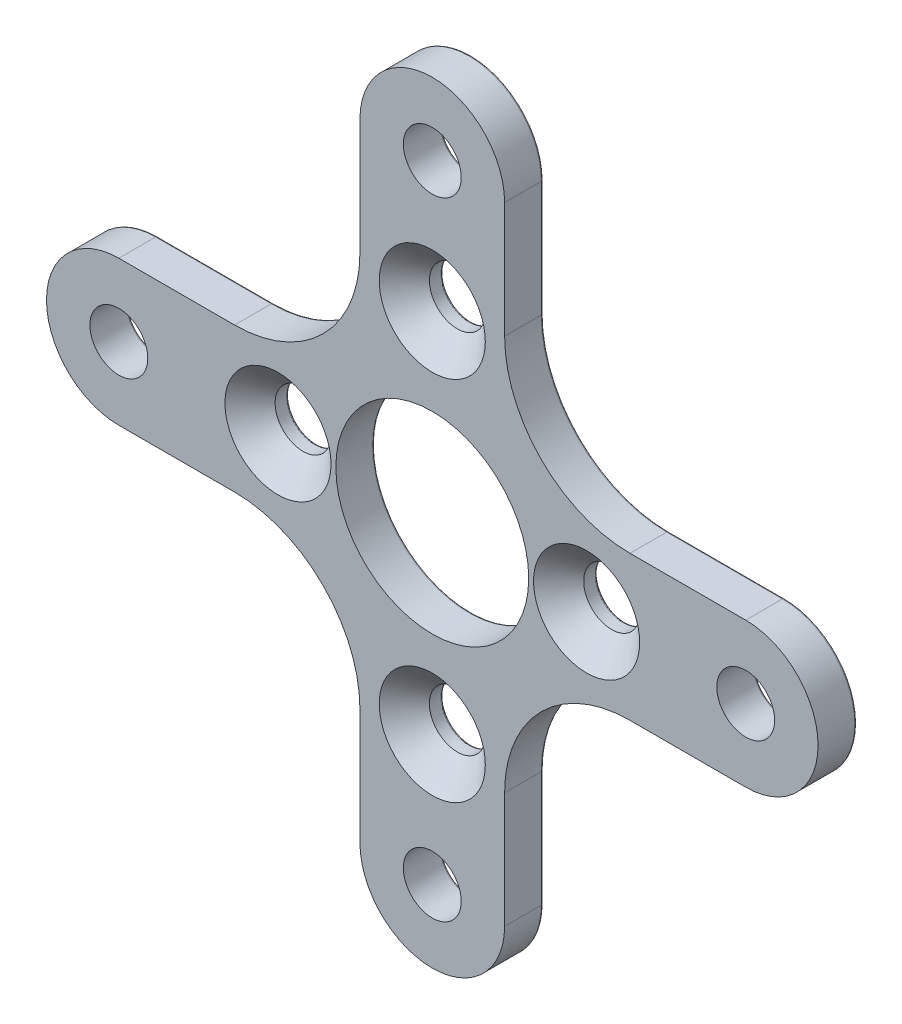
SolidWorks part; units mm, degrees
material "1060-H18 Rod (SS)"
ref_plane "Plan de face" through (0, 0, 0) normal (0, 0, 1) x (1, 0, 0)
ref_plane "Plan de dessus" through (0, 0, 0) normal (0, 1, 0) x (1, 0, 0)
ref_plane "Plan de droite" through (0, 0, 0) normal (1, 0, 0) x (0, 0, -1)
sketch "Esquisse1" plane through (0, 0, 0) normal (0, 0, 1) x (1, 0, 0)
  line L0 (-3.75, 16.25) -> (-3.75, 10.25)
  line L1 (-10.25, 3.75) -> (-16.25, 3.75)
  line L2 (-3.75, 16.25) -> (0, 16.25) construction
  line L3 (-16.25, 3.75) -> (-16.25, 0) construction
  line L4 (0, -16.25) -> (0, 16.25) construction
  line L5 (-16.25, 0) -> (0, 0) construction
  line L6 (0, 20) -> (0, 16.25) construction
  line L7 (-16.25, 0) -> (-20, 0) construction
  line L8 (3.75, 16.25) -> (3.75, 10.25)
  line L9 (0, 16.25) -> (3.75, 16.25) construction
  line L10 (10.25, 3.75) -> (16.25, 3.75)
  line L11 (0, -20) -> (0, -16.25) construction
  line L12 (0, -16.25) -> (3.75, -16.25) construction
  line L13 (-16.25, -3.75) -> (-16.25, 0) construction
  line L14 (-3.75, -16.25) -> (0, -16.25) construction
  line L15 (10.25, -3.75) -> (16.25, -3.75)
  line L16 (3.75, -16.25) -> (3.75, -10.25)
  line L17 (-10.25, -3.75) -> (-16.25, -3.75)
  line L18 (-3.75, -16.25) -> (-3.75, -10.25)
  line L19 (0, 0) -> (20, 0) construction
  line L20 (16.25, 3.75) -> (16.25, -3.75) construction
  arc A0 (-16.25, -3.75) -> (-16.25, 3.75) centre (-16.25, 0) cw
  arc A1 (-3.75, 16.25) -> (3.75, 16.25) centre (0, 16.25) cw
  arc A2 (16.25, -3.75) -> (16.25, 3.75) centre (16.25, 0) ccw
  arc A3 (-3.75, -16.25) -> (3.75, -16.25) centre (0, -16.25) ccw
  circle A4 centre (0, 0) radius 5
  arc A5 (-10.25, -3.75) -> (-3.75, -10.25) centre (-10.25, -10.25) cw
  arc A6 (10.25, -3.75) -> (3.75, -10.25) centre (10.25, -10.25) ccw
  arc A7 (3.75, 10.25) -> (10.25, 3.75) centre (10.25, 10.25) ccw
  arc A8 (-3.75, 10.25) -> (-10.25, 3.75) centre (-10.25, 10.25) cw
  circle A9 centre (0, 16.25) radius 1.5
  circle A10 centre (16.25, 0) radius 1.5
  circle A11 centre (-16.25, 0) radius 1.5
  circle A12 centre (0, -16.25) radius 1.5
  point P26 (-3.75, -3.75)
  point P29 (3.75, -3.75)
  point P32 (3.75, 3.75)
  point P35 (-3.75, 3.75)
  point P47 (0, 0)
  dimension "D3" = 20
  dimension "D4" = 20
  dimension "D5" = 10
  dimension "D6" = 6.5
  dimension "D7" = 3
  dimension "D1" = 3.75
  dimension "D2" = 3.75
  dimension "D8" = 16.25
  dimension "D9" = 4
extrude "Boss.-Extru.1" add sketch "Esquisse1" along normal mid plane 2
sketch "Esquisse2" plane through (0, 0, 1) normal (0, 0, 1) x (1, 0, 0)
  line L0 (0, 9.5) -> (0, 0) construction
  line L1 (0, 0) -> (8, 0) construction
  line L2 (0, 0) -> (0, -9.5) construction
  line L3 (0, 0) -> (-8, 0) construction
  point P0 (-8, 0)
  point P1 (0, 9.5)
  point P2 (8, 0)
  point P3 (0, -9.5)
  dimension "D1" = 16
  dimension "D2" = 19
  dimension "D3" = 9.5
  dimension "D4" = 8
hole_wizard "Fraisage pour vis à tête fraisée M2.51" positions "Esquisse3D1" profile "Esquisse3" countersink size "M2.5" standard "ISO" end condition up to next
sketch3d "Esquisse3D1"
  point P0 (-8, 0, 1)
  point P3 (0, 9.5, 1)
  point P6 (8, 0, 1)
  point P9 (0, -9.5, 1)
sketch "Esquisse3" plane through (-8, 0, 1) normal (1, 0, 0) x (0, -1, 0)
  line L0 (0, 0) -> (0, 2)
  line L1 (0, 2) -> (1.45, 2)
  line L2 (1.45, 2) -> (1.45, 1.3)
  line L3 (1.45, 1.3) -> (2.75, 0)
  line L5 (2.75, 0) -> (0, 0)
  line L6 (-1.45, 1.3) -> (-2.75, 0) construction
  line L11 (0, -6.35) -> (0, 107.95) construction
  dimension "Diamètre du perçage jusqu'au prochain" = 2.9
  dimension "Profondeur du perçage jusqu'au prochain" = 2
  dimension "Diamètre du fraisage entrant" = 5.5
  dimension "Angle du fraisage entrant" = 90
fillet "Congé1" radius 0.1 25 edges at (1.5, -16.25, -1) (1.5, 16.25, -1) (5, 0, -1) (-3.75, 13.25, -1) (-5.6538, 5.6538, -1) (-13.25, 3.75, -1) (-20, 0, -1) (-13.25, -3.75, -1) (-5.6538, -5.6538, -1) (-3.75, -13.25, -1) (0, -20, -1) (3.75, -13.25, -1) (5.6538, -5.6538, -1) (13.25, -3.75, -1) (20, 0, -1) (13.25, 3.75, -1) (5.6538, 5.6538, -1) (3.75, 13.25, -1) (0, 20, -1) (-14.75, 0, -1) (17.75, 0, -1) (-1.45, -9.5, -1) (6.55, 0, -1) (-1.45, 9.5, -1) (-9.45, 0, -1)
